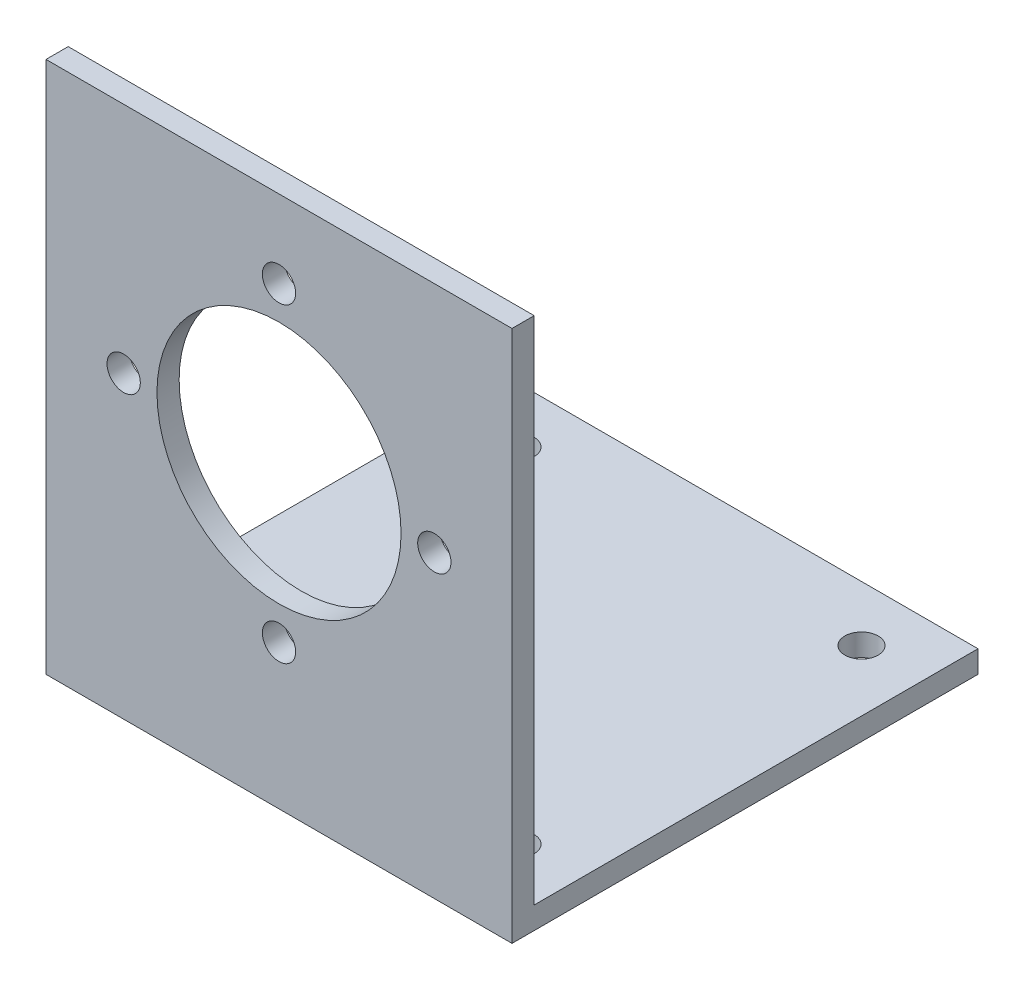
SolidWorks part; units mm, degrees
ref_plane "前视基准面" through (0, 0, 0) normal (0, 0, 1) x (1, 0, 0)
ref_plane "上视基准面" through (0, 0, 0) normal (0, 1, 0) x (1, 0, 0)
ref_plane "右视基准面" through (0, 0, 0) normal (1, 0, 0) x (0, 0, -1)
sketch "草图1" plane through (0, 0, 0) normal (1, 0, 0) x (0, 0, -1)
  line L1 (0, 0) -> (2, 0)
  line L2 (0, 0) -> (0, 48)
  line L3 (0, 48) -> (2, 48)
  line L4 (2, 2) -> (2, 48)
  line L5 (0, 0) -> (42, 0)
  line L6 (0, 0) -> (0, 2)
  line L7 (2, 2) -> (42, 2)
  line L8 (42, 0) -> (42, 2)
  dimension "D1" = 42
  dimension "D2" = 48
  dimension "D3" = 2
  dimension "D4" = 2
extrude "凸台-拉伸1" add sketch "草图1" along normal blind 42 contours L5 L8 L7 L4 L3 L2 L1
sketch "草图2" plane through (0, 0, -2) normal (0, 0, -1) x (-1, 0, 0)
  line L0 (0, 2) -> (0, 48) construction
  line L1 (-42, 48) -> (0, 48) construction
  circle A0 centre (-21, 27) radius 11
  dimension "D1" = 22
  dimension "D2" = 21
  dimension "D3" = 21
extrude "切除-拉伸1" cut sketch "草图2" against normal through all
sketch "草图3" plane through (0, 0, 0) normal (0, 0, 1) x (1, 0, 0)
  line L0 (42, 48) -> (0, 48) construction
  line L2 (21, 48) -> (21, 0) construction
  line L3 (42, 0) -> (0, 0) construction
  line L4 (21, 27) -> (32, 27) construction
  circle A0 centre (21, 41) radius 1.5
  circle A1 centre (21, 13) radius 1.5
  circle A2 centre (35, 27) radius 1.5
  circle A3 centre (7, 27) radius 1.5
  circle A4 centre (21, 27) radius 11 construction
  dimension "D1" = 3
  dimension "D2" = 28
  dimension "D3" = 28
  dimension "D4" = 14
  dimension "D5" = 14
extrude "切除-拉伸2" cut sketch "草图3" against normal through all
sketch "草图4" plane through (0, 2, 0) normal (0, 1, 0) x (1, 0, 0)
  line L0 (42, 2) -> (42, 42) construction
  line L1 (42, 42) -> (0, 42) construction
  circle A0 centre (5.5, 37) radius 1.5
  circle A1 centre (36.5, 37) radius 1.5
  circle A2 centre (36.5, 6) radius 1.5
  circle A3 centre (5.5, 6) radius 1.5
  dimension "D1" = 3
  dimension "D2" = 31
  dimension "D3" = 31
  dimension "D4" = 5.5
  dimension "D5" = 5
extrude "切除-拉伸3" cut sketch "草图4" against normal through all
